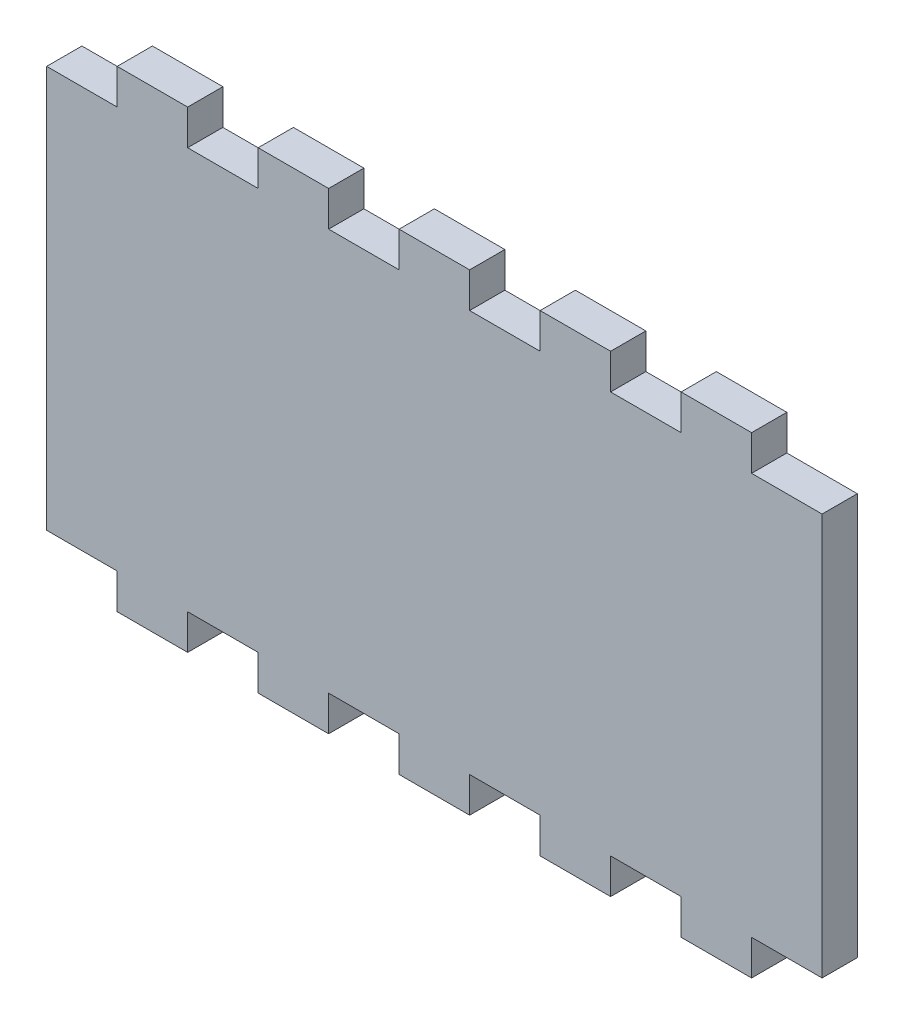
SolidWorks part; units mm, degrees
material "Acrylic (Medium-high impact)"
ref_plane "Front Plane" through (0, 0, 0) normal (0, 0, 1) x (1, 0, 0)
ref_plane "Top Plane" through (0, 0, 0) normal (0, 1, 0) x (1, 0, 0)
ref_plane "Right Plane" through (0, 0, 0) normal (1, 0, 0) x (0, 0, -1)
sketch "Sketch1" plane through (0, 0, 0) normal (0, 0, 1) x (1, 0, 0)
  line L0 (0, 3.175) -> (6.35, 3.175)
  line L1 (6.35, 3.175) -> (6.35, 0)
  line L2 (6.35, 0) -> (12.7, 0)
  line L3 (12.7, 0) -> (12.7, 3.175)
  line L4 (12.7, 3.175) -> (19.05, 3.175)
  line L5 (19.05, 3.175) -> (19.05, 0)
  line L6 (19.05, 0) -> (25.4, 0)
  line L7 (25.4, 0) -> (25.4, 3.175)
  line L8 (25.4, 3.175) -> (31.75, 3.175)
  line L9 (31.75, 3.175) -> (31.75, 0)
  line L10 (31.75, 0) -> (38.1, 0)
  line L11 (38.1, 0) -> (38.1, 3.175)
  line L12 (38.1, 3.175) -> (44.45, 3.175)
  line L13 (44.45, 3.175) -> (44.45, 0)
  line L14 (44.45, 0) -> (50.8, 0)
  line L15 (50.8, 0) -> (50.8, 3.175)
  line L16 (50.8, 3.175) -> (57.15, 3.175)
  line L17 (57.15, 3.175) -> (57.15, 0)
  line L18 (57.15, 0) -> (63.5, 0)
  line L19 (63.5, 0) -> (63.5, 3.175)
  line L20 (63.5, 3.175) -> (69.85, 3.175)
  line L21 (0, 3.175) -> (0, 39.37)
  line L22 (0, 39.37) -> (6.35, 39.37)
  line L23 (69.85, 3.175) -> (69.85, 39.37)
  line L24 (0, 21.2725) -> (69.85, 21.2725) construction
  line L25 (50.8, 39.37) -> (57.15, 39.37)
  line L26 (63.5, 42.545) -> (63.5, 39.37)
  line L27 (57.15, 42.545) -> (63.5, 42.545)
  line L28 (50.8, 42.545) -> (50.8, 39.37)
  line L29 (44.45, 42.545) -> (50.8, 42.545)
  line L30 (44.45, 39.37) -> (44.45, 42.545)
  line L31 (38.1, 42.545) -> (38.1, 39.37)
  line L32 (31.75, 42.545) -> (38.1, 42.545)
  line L33 (31.75, 39.37) -> (31.75, 42.545)
  line L34 (25.4, 42.545) -> (25.4, 39.37)
  line L35 (19.05, 42.545) -> (25.4, 42.545)
  line L36 (19.05, 39.37) -> (19.05, 42.545)
  line L37 (12.7, 42.545) -> (12.7, 39.37)
  line L38 (6.35, 42.545) -> (12.7, 42.545)
  line L39 (6.35, 39.37) -> (6.35, 42.545)
  line L40 (12.7, 39.37) -> (19.05, 39.37)
  line L41 (25.4, 39.37) -> (31.75, 39.37)
  line L42 (38.1, 39.37) -> (44.45, 39.37)
  line L43 (57.15, 39.37) -> (57.15, 42.545)
  line L44 (63.5, 39.37) -> (69.85, 39.37)
  dimension "D1" = 6.35
  dimension "D2" = 3.175
  dimension "D3" = 6.35
  dimension "D5" = 36.195
extrude "Boss-Extrude1" add sketch "Sketch1" along normal blind 3.175
